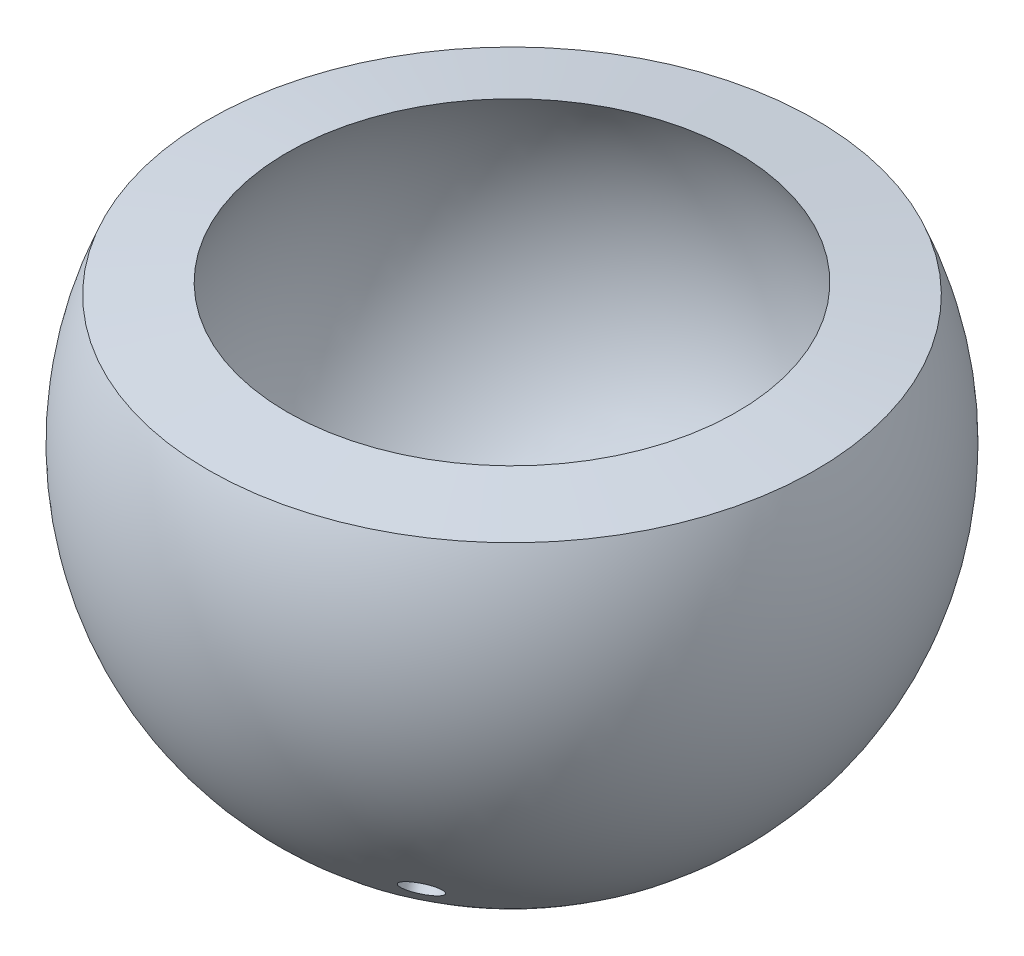
SolidWorks part; units mm, degrees
ref_plane "Front Plane" through (0, 0, 0) normal (0, 0, 1) x (1, 0, 0)
ref_plane "Top Plane" through (0, 0, 0) normal (0, 1, 0) x (1, 0, 0)
ref_plane "Right Plane" through (0, 0, 0) normal (1, 0, 0) x (0, 0, -1)
sketch "Sketch1" plane through (0, 0, 0) normal (0, 0, 1) x (1, 0, 0)
  line L0 (0, 0) -> (-40.927, 25.3332)
  line L1 (0, 0) -> (40.927, 25.3332)
  line L2 (-32.828, 20.32) -> (32.828, 20.32) construction
  line L3 (0, 48.133) -> (0, -48.133)
  line L4 (-44.3382, 18.7325) -> (44.3382, 18.7325) construction
  line L5 (0, -38.608) -> (12.7, -38.608)
  line L6 (0, -38.608) -> (0, -140.208)
  line L7 (0, -140.208) -> (12.7, -140.208)
  line L8 (12.7, -38.608) -> (12.7, -140.208)
  line L9 (-32.828, 20.32) -> (-44.3382, 18.7325)
  line L10 (32.828, 20.32) -> (44.3382, 18.7325)
  circle A0 centre (0, 0) radius 38.608
  circle A1 centre (0, 0) radius 48.133
  dimension "D1" = 77.216
  dimension "D2" = 96.266
  dimension "D3" = 12.7
  dimension "D4" = 20.32
  dimension "D5" = 101.6
  dimension "D6" = 1.5875
revolve "Revolve1" add sketch "Sketch1" angle 360 about L3
hole_wizard "#7 (0.201) Diameter Hole1" positions "3DSketch4" profile "Sketch5" hole size "#7" standard "ANSI Inch" end condition up to next
sketch3d "3DSketch4"
  line L0 (0, 0, 0) -> (0, -31.75, 0) construction
  point P0 (-36.1763, -31.75, 0)
  dimension "D1" = 31.75
sketch "Sketch5" plane through (-36.1763, -31.75, 0) normal (0, 0, 1) x (0.6596, -0.7516, 0)
  line L0 (0, 0) -> (0, 101.1769)
  line L1 (0, 101.1769) -> (2.5527, 101.1769)
  line L2 (2.5527, 101.1769) -> (2.5527, 0)
  line L5 (2.5527, 0) -> (0, 0)
  line L11 (0, -6.35) -> (0, 107.95) construction
  dimension "Thru Hole Dia." = 5.1054
  dimension "Thru Hole Depth" = 101.1769
pattern_circular "CirPattern1" count 3 over 360 about axis through (0, 18.7325, 0) along (0, 1, 0) of "#7 (0.201) Diameter Hole1"
sketch "Sketch7" plane through (0, 0, 0) normal (0, 1, 0) x (1, 0, 0)
  circle A0 centre (0, 0) radius 2.54
  dimension "D1" = 5.08
extrude "Cut-Extrude1" cut sketch "Sketch7" against normal through all
